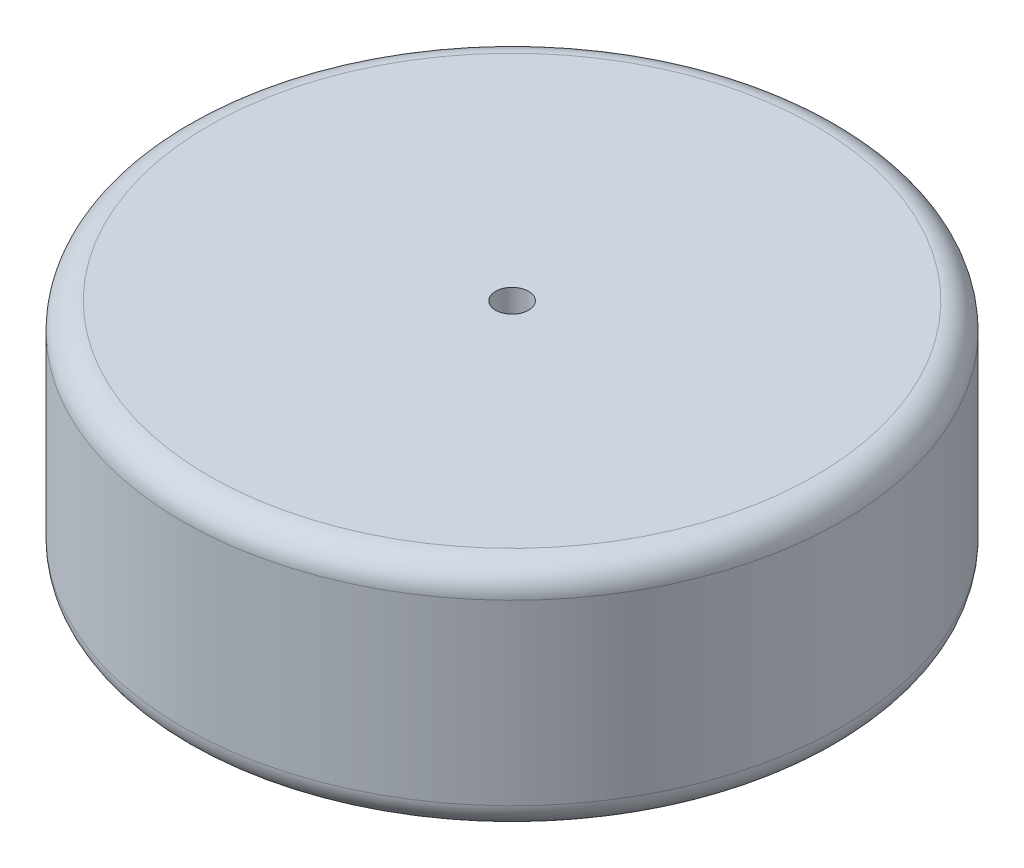
SolidWorks part; units mm, degrees
ref_plane "前视基准面" through (0, 0, 0) normal (0, 0, 1) x (1, 0, 0)
ref_plane "上视基准面" through (0, 0, 0) normal (0, 1, 0) x (1, 0, 0)
ref_plane "右视基准面" through (0, 0, 0) normal (1, 0, 0) x (0, 0, -1)
sketch "草图1" plane through (0, 0, 0) normal (0, 1, 0) x (1, 0, 0)
  circle A0 centre (0, 0) radius 100
  dimension "D1" = 200
extrude "凸台-拉伸1" add sketch "草图1" along normal blind 70
fillet "圆角1" radius 8 2 edges at (0, 0, 100) (0, 70, 100)
sketch "草图2" plane through (0, 0, 0) normal (0, -1, 0) x (1, 0, 0)
  circle A0 centre (0, 0) radius 5
  dimension "D1" = 10
extrude "切除-拉伸1" cut sketch "草图2" against normal through all
